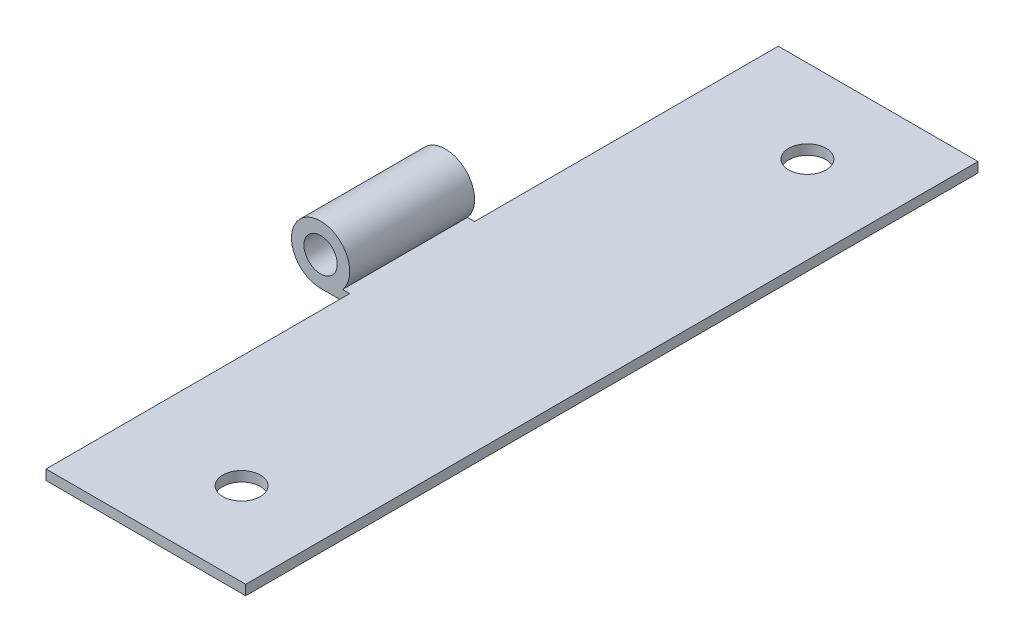
SolidWorks part; units mm, degrees
ref_plane "Front Plane" through (0, 0, 0) normal (0, 0, 1) x (1, 0, 0)
ref_plane "Top Plane" through (0, 0, 0) normal (0, 1, 0) x (1, 0, 0)
ref_plane "Right Plane" through (0, 0, 0) normal (1, 0, 0) x (0, 0, -1)
sketch "Sketch1" plane through (0, 0, 0) normal (0, 1, 0) x (1, 0, 0)
  line L1 (-12, -44) -> (12, -44)
  line L2 (-12, -44) -> (-12, 44)
  line L3 (-12, 44) -> (12, 44)
  line L4 (12, -44) -> (12, 44)
  line L5 (-12, -44) -> (12, 44) construction
  line L6 (-12, 44) -> (12, -44) construction
  point P0 (0, 0)
  dimension "D1" = 88
  dimension "D2" = 24
extrude "Boss-Extrude1" add sketch "Sketch1" along normal blind 1.2
sketch "Sketch2" plane through (0, 0, 0) normal (0, 0, 1) x (1, 0, 0)
  line L0 (-12, 0) -> (12, 0) construction
  line L2 (12, 1.2) -> (12, 0) construction
  line L3 (-12, 0) -> (-15.5, 0)
  line L4 (-12, 1.2) -> (-12.8618, 1.2)
  line L5 (-12, 1.2) -> (-12, 0)
  arc A0 (-12.8618, 1.2) -> (-15.5, 0) centre (-15.5, 3.5) ccw
  circle A1 centre (-15.5, 3.5) radius 2
  point P5 (-19, 3.5)
  dimension "D2" = 7
  dimension "D3" = 4
  dimension "D1" = 27.5
extrude "Boss-Extrude2" add sketch "Sketch2" along normal mid plane 15
sketch "Sketch4" plane through (0, 1.2, 0) normal (0, 1, 0) x (1, 0, 0)
  line L0 (1.5, -44) -> (1.5, 44) construction
  line L1 (-12, -44) -> (12, -44) construction
  line L2 (12, 44) -> (-12, 44) construction
  line L3 (0, 0) -> (12, 0) construction
  line L4 (12, -44) -> (12, 44) construction
  circle A0 centre (1.5, 34) radius 2.25
  circle A1 centre (1.5, -34) radius 2.25
  point P6 (-19, 7.5)
  point P15 (-15.5, 7.5)
  dimension "D2" = 4.5
  dimension "D3" = 34
  dimension "D1" = 17
extrude "Cut-Extrude2" cut sketch "Sketch4" against normal through all
